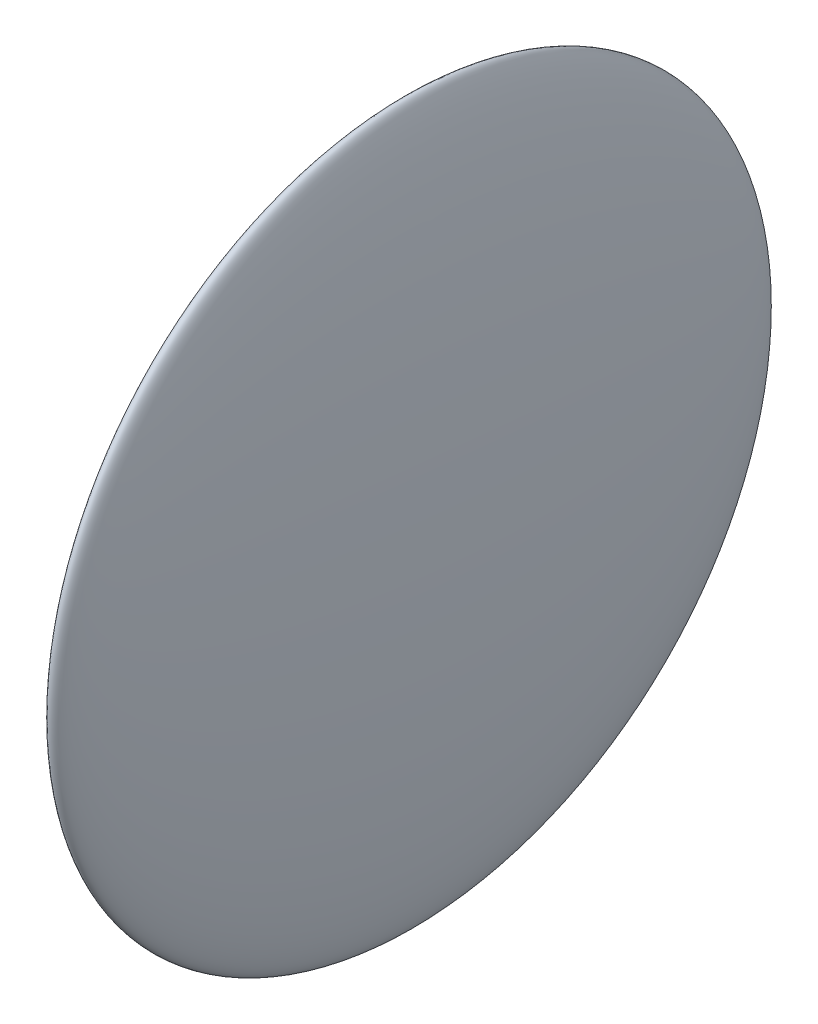
SolidWorks part; units mm, degrees
ref_plane "Ön Düzlem" through (0, 0, 0) normal (0, 0, 1) x (1, 0, 0)
ref_plane "Üst Düzlem" through (0, 0, 0) normal (0, 1, 0) x (1, 0, 0)
ref_plane "Sağ Düzlem" through (0, 0, 0) normal (1, 0, 0) x (0, 0, -1)
sketch "Çizim1" plane through (0, 0, 0) normal (0, 0, 1) x (1, 0, 0)
  line L1 (-0.35, 3.75) -> (0.35, 3.75)
  line L2 (-1.702, 3.75) -> (2.4869, 3.75) construction
  ellipse E0 centre (0, 3.75) end of major axis (0, 0) minor radius 0.35 (0.35, 3.75) -> (-0.35, 3.75) ccw
  dimension "D1" = 3.75
  dimension "D2" = 0.35
revolve "Döndür5" add sketch "Çizim1" angle 360 about L2
